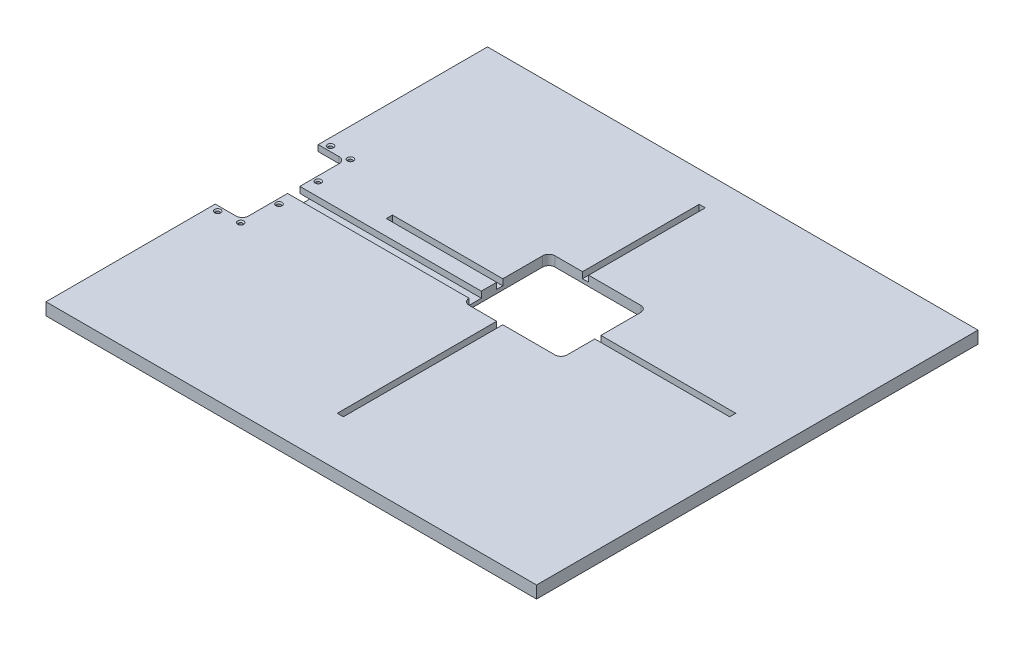
SolidWorks part; units mm, degrees
ref_plane "Front Plane" through (0, 0, 0) normal (0, 0, 1) x (1, 0, 0)
ref_plane "Top Plane" through (0, 0, 0) normal (0, 1, 0) x (1, 0, 0)
ref_plane "Right Plane" through (0, 0, 0) normal (1, 0, 0) x (0, 0, -1)
sketch "Sketch1" plane through (0, 0, 0) normal (0, 1, 0) x (1, 0, 0)
  line L0 (0, 160) -> (0, 0) construction
  line L1 (-220, 180) -> (180, 180)
  line L2 (-220, 180) -> (-220, -180)
  line L3 (-220, -180) -> (180, -180)
  line L4 (180, 180) -> (180, -180)
  line L5 (-160, 160) -> (160, 160) construction
  line L6 (-160, 160) -> (-160, -160) construction
  line L7 (-160, -160) -> (160, -160) construction
  line L8 (160, 160) -> (160, -160) construction
  line L9 (0, 0) -> (160, 0) construction
  line L10 (0, 0) -> (-160, 0) construction
  line L11 (0, 0) -> (0, -160) construction
  line L12 (-120, 160) -> (-120, -160) construction
  line L13 (-80, 160) -> (-80, -160) construction
  line L14 (-40, 160) -> (-40, -160) construction
  line L15 (0, 160) -> (0, -160) construction
  line L16 (40, 160) -> (40, -160) construction
  line L17 (80, 160) -> (80, -160) construction
  line L18 (120, 160) -> (120, -160) construction
  line L19 (-160, 120) -> (160, 120) construction
  line L20 (-160, 80) -> (160, 80) construction
  line L21 (-160, 40) -> (160, 40) construction
  line L22 (-160, 0) -> (160, 0) construction
  line L23 (-160, -40) -> (160, -40) construction
  line L24 (-160, -80) -> (160, -80) construction
  line L25 (-160, -120) -> (160, -120) construction
  dimension "D1" = 360
  dimension "D2" = 400
  dimension "D3" = 320
  dimension "D4" = 320
  dimension "D5" = 20
extrude "Boss-Extrude1" add sketch "Sketch1" against normal blind 10
sketch "Sketch3" plane through (0, 0, 0) normal (0, 1, 0) x (1, 0, 0)
  line L0 (-220, 180) -> (-220, -180) construction
  line L1 (-45, 60) -> (25, 60)
  line L2 (-50, 55) -> (-50, -5)
  line L3 (-45, -10) -> (25, -10)
  line L4 (30, 55) -> (30, -5)
  line L5 (180, 180) -> (-220, 180) construction
  arc A0 (-50, -5) -> (-45, -10) centre (-45, -5) ccw
  arc A1 (25, -10) -> (30, -5) centre (25, -5) ccw
  arc A2 (25, 60) -> (30, 55) centre (25, 55) cw
  arc A3 (-45, 60) -> (-50, 55) centre (-45, 55) ccw
  point P10 (-50, -10)
  point P15 (30, 60)
  point P18 (-50, 60)
  dimension "D5" = 5
  dimension "D1" = 80
  dimension "D2" = 70
  dimension "D3" = 170
  dimension "D4" = 120
extrude "Cut-Extrude1" cut sketch "Sketch3" against normal through all
sketch "Sketch4" plane through (0, -10, 0) normal (0, -1, 0) x (1, 0, 0)
  line L0 (-45, 10) -> (25, 10) construction
  line L1 (-52, 18) -> (32, 18)
  line L2 (-58, 12) -> (-58, -62)
  line L3 (-52, -68) -> (32, -68)
  line L4 (38, 12) -> (38, -62)
  line L5 (30, 5) -> (30, -55) construction
  line L6 (25, -60) -> (-45, -60) construction
  line L7 (-50, -55) -> (-50, 5) construction
  arc A0 (-52, 18) -> (-58, 12) centre (-52, 12) ccw
  arc A1 (-58, -62) -> (-52, -68) centre (-52, -62) ccw
  arc A2 (32, -68) -> (38, -62) centre (32, -62) ccw
  arc A3 (32, 18) -> (38, 12) centre (32, 12) cw
  dimension "D5" = 6
  dimension "D1" = 8
  dimension "D2" = 8
  dimension "D3" = 8
  dimension "D4" = 8
extrude "Cut-Extrude2" cut sketch "Sketch4" against normal blind 2
sketch "Sketch5" plane through (0, -8, 0) normal (0, -1, 0) x (1, 0, 0)
  circle A0 centre (32, 12) radius 1.5
  circle A1 centre (-52, 12) radius 1.5
  circle A2 centre (32, -62) radius 1.5
  circle A3 centre (-52, -62) radius 1.5
  dimension "D1" = 3
  dimension "D2" = 3
  dimension "D3" = 3
  dimension "D4" = 3
extrude "Cut-Extrude3" cut sketch "Sketch5" against normal blind 3
sketch "Sketch9" plane through (0, -10, 0) normal (0, 1, 0) x (1, 0, 0)
  line L0 (-220, 180) -> (-220, -180) construction
  line L1 (-220, 50) -> (-195, 50)
  line L2 (-220, 50) -> (-220, -50)
  line L3 (-220, -50) -> (-195, -50)
  line L4 (-190, 45) -> (-190, -45)
  line L5 (-190, 0) -> (-160, 0) construction
  arc A0 (-195, -50) -> (-190, -45) centre (-195, -45) ccw
  arc A1 (-195, 50) -> (-190, 45) centre (-195, 45) cw
  point P11 (-190, -50)
  point P14 (-190, 50)
  dimension "D3" = 5
  dimension "D1" = 30
  dimension "D2" = 100
extrude "Cut-Extrude6" cut sketch "Sketch9" along normal blind 5
sketch "Sketch10" plane through (0, -5, 0) normal (0, -1, 0) x (-1, 0, 0)
  line L0 (220, 180) -> (220, -180) construction
  line L2 (220, 42) -> (220, -42)
  line L8 (198, 37) -> (198, -37)
  line L9 (220, -42) -> (203, -42)
  line L10 (220, 42) -> (203, 42)
  line L11 (195, 50) -> (220, 50) construction
  line L12 (220, -50) -> (195, -50) construction
  line L13 (190, -45) -> (190, 45) construction
  arc A2 (203, 42) -> (198, 37) centre (203, 37) ccw
  arc A3 (203, -42) -> (198, -37) centre (203, -37) cw
  dimension "D4" = 5
  dimension "D5" = 5
  dimension "D1" = 8
  dimension "D2" = 8
  dimension "D3" = 8
extrude "Cut-Extrude7" cut sketch "Sketch10" against normal blind 5
sketch "Sketch11" plane through (0, -5, 0) normal (0, -1, 0) x (-1, 0, 0)
  line L0 (160, 0) -> (220, 0) construction
  line L1 (220, 180) -> (220, -180) construction
  line L2 (190, -45) -> (190, 45) construction
  line L3 (194, 46) -> (194, 16) construction
  line L4 (214, -46) -> (194, -46) construction
  line L5 (194, -46) -> (194, -16) construction
  line L6 (214, 46) -> (194, 46) construction
  line L7 (220, 42) -> (203, 42) construction
  circle A0 centre (214, 46) radius 1.5
  circle A2 centre (194, 16) radius 1.5
  circle A3 centre (196.5, 44.75) radius 1.5
  circle A4 centre (196.5, -44.75) radius 1.5
  circle A5 centre (194, -16) radius 1.5
  circle A6 centre (214, -46) radius 1.5
  dimension "D1" = 3
  dimension "D2" = 3
  dimension "D3" = 3
  dimension "D7" = 16
  dimension "D8" = 4
  dimension "D9" = 2.5
  dimension "D4" = 6
  dimension "D10" = 2.5
  dimension "D5" = 4
  dimension "D6" = 30
extrude "Cut-Extrude8" cut sketch "Sketch11" against normal through all
sketch "Sketch14" plane through (0, 0, 0) normal (0, 1, 0) x (1, 0, 0)
  line L0 (-198, 37) -> (-198, -37) construction
  line L1 (-198, 5) -> (-38, 5)
  line L2 (-198, 5) -> (-198, -5)
  line L3 (-198, -5) -> (-38, -5)
  line L4 (-38, 5) -> (-38, -5)
  line L5 (-38, 0) -> (0, 0) construction
  dimension "D1" = 10
  dimension "D2" = 160
extrude "Cut-Extrude9" cut sketch "Sketch14" against normal blind 5
sketch "Sketch15" plane through (0, 0, 0) normal (0, 1, 0) x (1, 0, 0)
  line L1 (-22.5, 155.1504) -> (-17.5, 155.1504)
  line L2 (-22.5, 155.1504) -> (-22.5, -140)
  line L3 (-22.5, -140) -> (-17.5, -140)
  line L4 (-17.5, 155.1504) -> (-17.5, -140)
  line L5 (-160, 160) -> (-160, -160) construction
  line L6 (-140, 22.5) -> (140, 22.5)
  line L7 (-140, 22.5) -> (-140, 17.5)
  line L8 (-140, 17.5) -> (140, 17.5)
  line L9 (140, 22.5) -> (140, 17.5)
  line L10 (160, 160) -> (160, -160) construction
  line L11 (-160, 160) -> (160, 160) construction
  line L12 (-160, -160) -> (160, -160) construction
  line L14 (-40, 160) -> (-40, -160) construction
  line L15 (-160, 40) -> (160, 40) construction
  line M12 (-45, 60) -> (25, 60)
  line M16 (25, -10) -> (-45, -10)
  dimension "D1" = 5
  dimension "D2" = 5
  dimension "D3" = 20
  dimension "D4" = 20
  dimension "D5" = 4.8496
  dimension "D6" = 20
  dimension "D7" = 17.5
  dimension "D8" = 17.5
extrude "Cut-Extrude10" cut sketch "Sketch15" against normal blind 5 contours L4 L1 L2 M12 | L4 L2 L3 M16 | L8 L2 L4 M16 | L2 L6 L4 M12 | L2 L8 L4 L6
chamfer "Chamfer2" distance 1 angle 45 6 edges at (-214, 0, 47.5) (-196.5, 0, 46.25) (-194, 0, 17.5) (-194, 0, -17.5) (-196.5, 0, -46.25) (-214, 0, -47.5)
